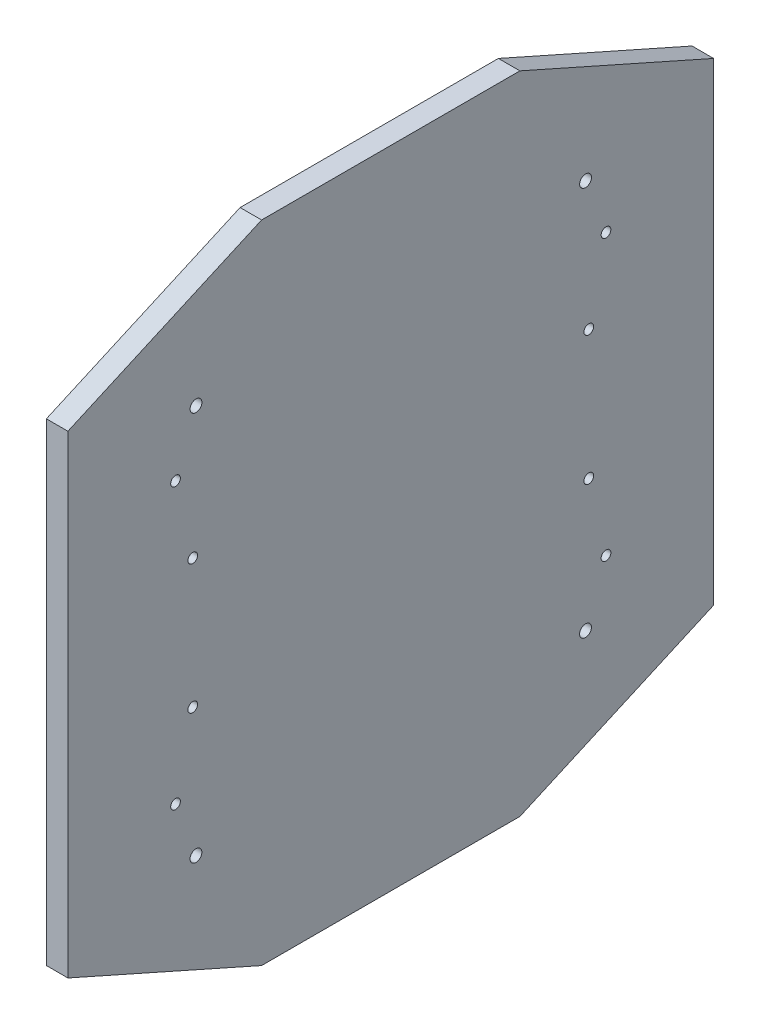
SolidWorks part; units mm, degrees
ref_plane "前视基准面" through (0, 0, 0) normal (0, 0, 1) x (1, 0, 0)
ref_plane "上视基准面" through (0, 0, 0) normal (0, 1, 0) x (1, 0, 0)
ref_plane "右视基准面" through (0, 0, 0) normal (1, 0, 0) x (0, 0, -1)
sketch "草图1" plane through (0, 0, 0) normal (1, 0, 0) x (0, 0, -1)
  line L0 (-150, -110) -> (-150, 110)
  line L1 (-150, 110) -> (-60, 150)
  line L2 (-60, 150) -> (60, 150)
  line L3 (0, 0) -> (0, 56460.0367) construction
  line L4 (-150, -110) -> (-60, -150)
  line L5 (-60, -150) -> (60, -150)
  line L6 (150, -110) -> (60, -150)
  line L7 (150, 110) -> (60, 150)
  line L8 (150, -110) -> (150, 110)
  point P10 (0, -150)
  point P12 (0, 150)
  dimension "D1" = 300
  dimension "D2" = 300
  dimension "D3" = 120
  dimension "D4" = 120
  dimension "D5" = 220
  dimension "D6" = 40
  dimension "D7" = 150
extrude "凸台-拉伸1" add sketch "草图1" along normal blind 10
sketch "草图2" plane through (10, 0, 0) normal (1, 0, 0) x (0, 0, -1)
  line L0 (0, 0) -> (0, 50000) construction
  circle A0 centre (92, 30) radius 2.25
  circle A1 centre (92, -30) radius 2.25
  circle A2 centre (100, 65) radius 2.25
  circle A3 centre (100, -65) radius 2.25
  circle A4 centre (-100, -65) radius 2.25
  circle A5 centre (-100, 65) radius 2.25
  circle A6 centre (-92, -30) radius 2.25
  circle A7 centre (-92, 30) radius 2.25
  dimension "D1" = 130
  dimension "D7" = 4.5
  dimension "D2" = 60
  dimension "D3" = 30
  dimension "D4" = 65
  dimension "D5" = 100
  dimension "D6" = 92
extrude "切除-拉伸1" cut sketch "草图2" against normal blind 10
sketch "草图3" plane through (10, 0, 0) normal (1, 0, 0) x (0, 0, -1)
  line L1 (-90.5, 90.5) -> (90.5, 90.5) construction
  line L2 (-90.5, 90.5) -> (-90.5, -90.5) construction
  line L3 (-90.5, -90.5) -> (90.5, -90.5) construction
  line L4 (90.5, 90.5) -> (90.5, -90.5) construction
  circle A0 centre (-90.5, 90.5) radius 2.75
  circle A1 centre (90.5, 90.5) radius 2.75
  circle A2 centre (-90.5, -90.5) radius 2.75
  circle A3 centre (90.5, -90.5) radius 2.75
  dimension "D4" = 5.5
  dimension "D1" = 181
  dimension "D2" = 90.5
  dimension "D3" = 90.5
extrude "切除-拉伸2" cut sketch "草图3" against normal blind 10
